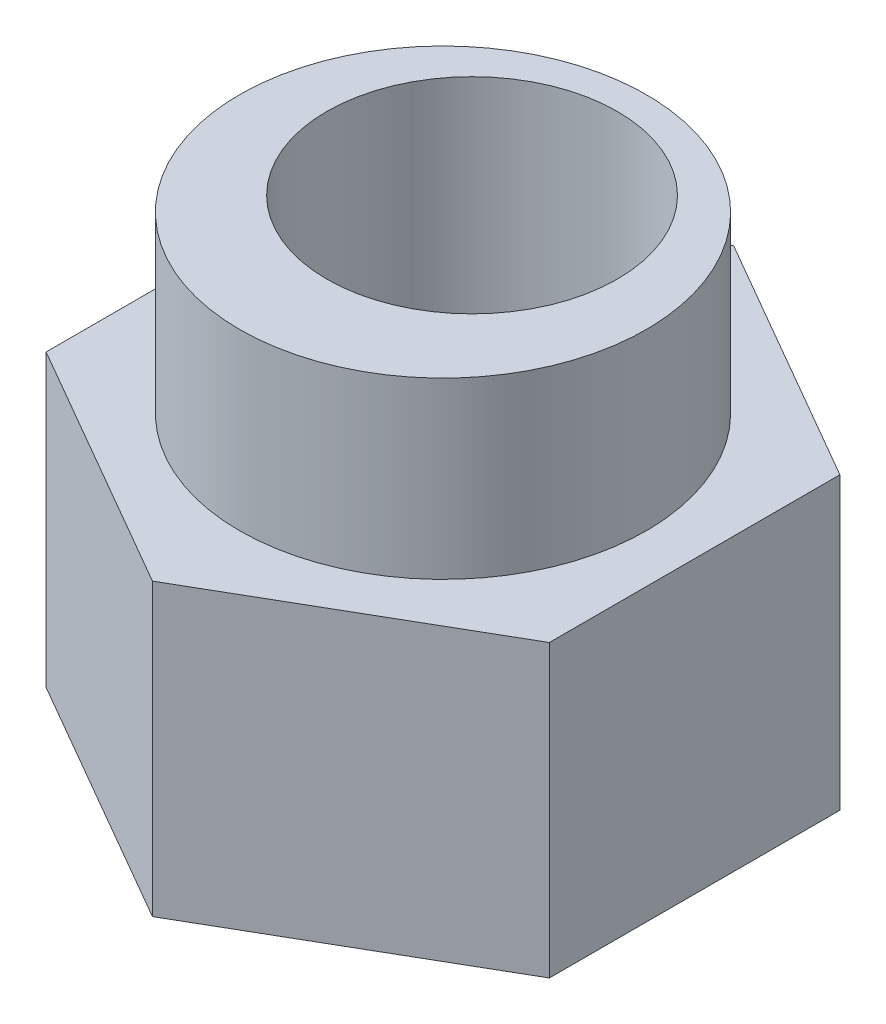
SolidWorks part; units mm, degrees
ref_plane "Front Plane" through (0, 0, 0) normal (0, 0, 1) x (1, 0, 0)
ref_plane "Top Plane" through (0, 0, 0) normal (0, 1, 0) x (1, 0, 0)
ref_plane "Right Plane" through (0, 0, 0) normal (1, 0, 0) x (0, 0, -1)
sketch "Sketch1" plane through (0, 0, 0) normal (0, 1, 0) x (1, 0, 0)
  line L1 (4.3301, 2.5) -> (0, 5)
  line L2 (0, 5) -> (-4.3301, 2.5)
  line L3 (-4.3301, 2.5) -> (-4.3301, -2.5)
  line L4 (-4.3301, -2.5) -> (0, -5)
  line L5 (0, -5) -> (4.3301, -2.5)
  line L6 (4.3301, -2.5) -> (4.3301, 2.5)
  circle A0 centre (0, 0) radius 4.3301 construction
  dimension "D1" = 10
extrude "Boss-Extrude1" add sketch "Sketch1" along normal blind 8
sketch "Sketch2" plane through (0, 8, 0) normal (0, 1, 0) x (1, 0, 0)
  line L0 (0, 5) -> (0, -5) construction
  circle A0 centre (0, 0.5) radius 2.5
  dimension "D2" = 5
  dimension "D1" = 4.5
extrude "Cut-Extrude1" cut sketch "Sketch2" against normal blind 8
sketch "Sketch3" plane through (0, 8, 0) normal (0, 1, 0) x (1, 0, 0)
  line L0 (0, 5) -> (0, -5) construction
  line L1 (-4.3301, 2.5) -> (-4.3301, -2.5) construction
  line L2 (-4.3301, 2.5) -> (-4.3301, -2.5)
  line L3 (0, 5) -> (-4.3301, 2.5) construction
  line L4 (0, 5) -> (-4.3301, 2.5)
  line L5 (-4.3301, -2.5) -> (0, -5) construction
  line L6 (-4.3301, -2.5) -> (0, -5)
  line L7 (0, -5) -> (4.3301, -2.5) construction
  line L8 (0, -5) -> (4.3301, -2.5)
  line L9 (4.3301, -2.5) -> (4.3301, 2.5) construction
  line L10 (4.3301, -2.5) -> (4.3301, 2.5)
  line L11 (4.3301, 2.5) -> (0, 5) construction
  line L12 (4.3301, 2.5) -> (0, 5)
  circle A0 centre (0, 0) radius 3.5
  dimension "D2" = 7
  dimension "D1" = 5
extrude "Cut-Extrude2" cut sketch "Sketch3" against normal blind 3
